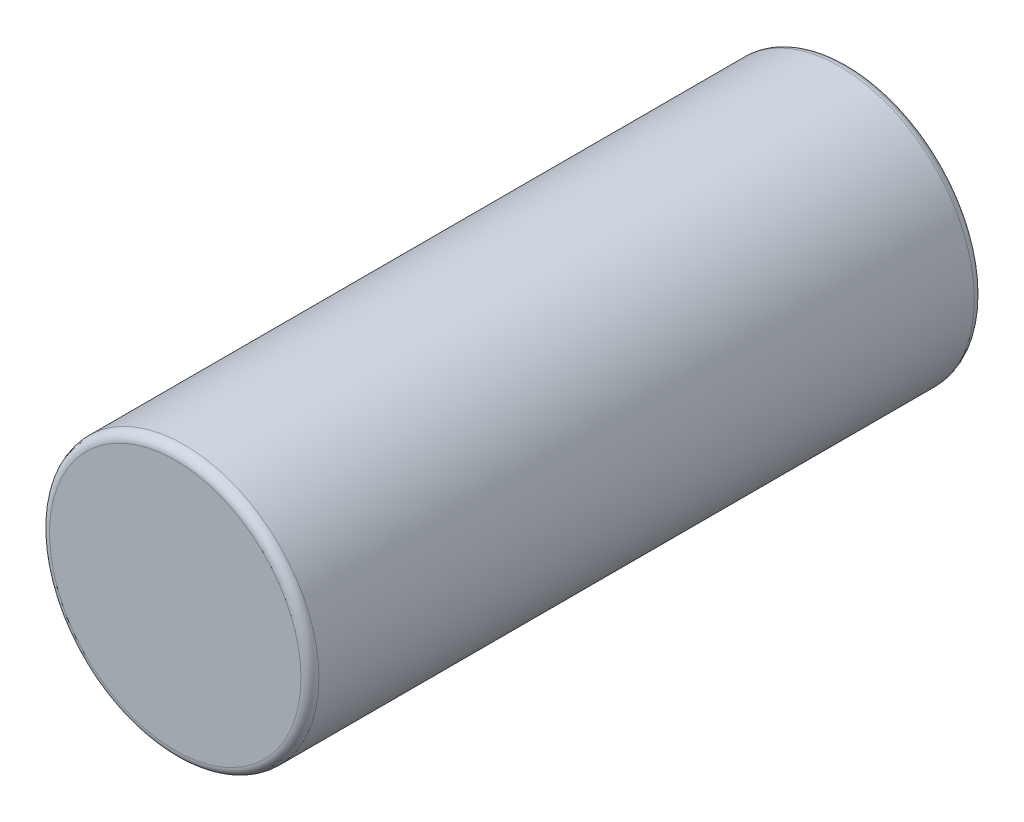
SolidWorks part; units mm, degrees
ref_plane "정면" through (0, 0, 0) normal (0, 0, 1) x (1, 0, 0)
ref_plane "윗면" through (0, 0, 0) normal (0, 1, 0) x (1, 0, 0)
ref_plane "우측면" through (0, 0, 0) normal (1, 0, 0) x (0, 0, -1)
sketch "스케치1" plane through (0, 0, 0) normal (0, 0, 1) x (1, 0, 0)
  circle A0 centre (0, 0) radius 3
  dimension "D1" = 6
extrude "보스-돌출1" add sketch "스케치1" along normal blind 15
fillet "필렛1" radius 0.2 2 edges at (3, 0, 0) (3, 0, 15)
